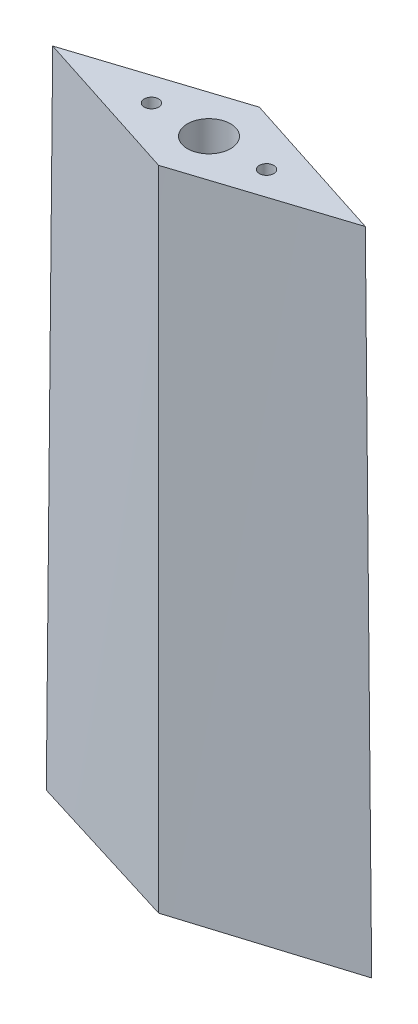
SolidWorks part; units mm, degrees
ref_plane "Front Plane" through (0, 0, 0) normal (0, 0, 1) x (1, 0, 0)
ref_plane "Top Plane" through (0, 0, 0) normal (0, 1, 0) x (1, 0, 0)
ref_plane "Right Plane" through (0, 0, 0) normal (1, 0, 0) x (0, 0, -1)
sketch "Sketch1" plane through (0, 0, 0) normal (0, 0, 1) x (1, 0, 0)
  line L0 (142.4212, 465.168) -> (219.716, 465.168)
  line L1 (219.716, 465.168) -> (213.5025, 1096.9676)
  line L2 (213.5025, 1096.9676) -> (181.0686, 1174.3372)
  line L3 (181.0686, 1174.3372) -> (148.6348, 1096.9676)
  line L4 (148.6348, 1096.9676) -> (142.4212, 465.168)
  point P2 (181.0686, 465.168)
extrude "Boss-Extrude1" add sketch "Sketch1" along normal blind 11.1125 and the other way blind 11.1125
sketch "Sketch2" plane through (0, 465.168, 0) normal (0, -1, 0) x (1, 0, 0)
  line L0 (142.4212, 0) -> (181.0686, 11.1125)
  line L1 (142.4212, -11.1125) -> (142.4212, 11.1125) construction
  line L2 (142.4212, 11.1125) -> (219.716, 11.1125) construction
  line L3 (181.0686, 11.1125) -> (219.716, 0)
  line L4 (219.716, -11.1125) -> (219.716, 11.1125) construction
  line L8 (142.4212, 0) -> (137.8486, 0)
  line L9 (137.8486, 0) -> (137.8486, 15.2584)
  line L10 (137.8486, 15.2584) -> (222.7051, 15.2584)
  line L11 (222.7051, 15.2584) -> (222.7051, 0)
  line L12 (222.7051, 0) -> (219.716, 0)
ref_plane "Plane1" through (0, 1096.9676, 0) normal (0, 1, 0) x (1, 0, 0)
sketch "Sketch3" plane through (0, 1096.9676, 0) normal (0, 1, 0) x (1, 0, 0)
  line L1 (148.6348, 11.1125) -> (148.6348, -11.1125) construction
  line L3 (213.5025, 11.1125) -> (213.5025, -11.1125) construction
  line L4 (213.5025, 0) -> (181.0686, -11.1125)
  line L5 (181.0686, -11.1125) -> (148.6348, 0)
  line L6 (148.6348, 0) -> (137.8486, 0)
  line L7 (137.8486, 0) -> (137.8486, -15.2584)
  line L8 (137.8486, -15.2584) -> (222.7051, -15.2584)
  line L9 (222.7051, -15.2584) -> (222.7051, 0)
  line L10 (222.7051, 0) -> (213.5025, 0)
loft "Cut-Loft1" cut profiles "Sketch2", "Sketch3"
mirror "Mirror1" about plane through (0, 0, 0) normal (0, 0, 1) of "Cut-Loft1"
ref_plane "Plane2" through (-32.1031, 13.4578, 93.6987) normal (-0.3212, 0.1346, 0.9374) x (0.947, 0.0457, 0.3179)
sketch "Sketch5" plane through (-32.1031, 13.4578, 93.6987) normal (-0.3212, 0.1346, 0.9374) x (0.947, 0.0457, 0.3179)
  line L1 (164.4105, 1280.8293) -> (274.288, 1280.8293)
  line L2 (164.4105, 1280.8293) -> (164.4105, 997.7782)
  line L3 (164.4105, 997.7782) -> (274.288, 997.7782)
  line L4 (274.288, 1280.8293) -> (274.288, 997.7782)
extrude "Cut-Extrude2" cut sketch "Sketch5" along normal through all
ref_plane "Plane3" through (69.4583, 29.1174, 202.7265) normal (0.3212, 0.1346, 0.9374) x (0.947, -0.0457, -0.3179)
sketch "Sketch6" plane through (69.4583, 29.1174, 202.7265) normal (0.3212, 0.1346, 0.9374) x (0.947, -0.0457, -0.3179)
  line L1 (57.1921, 1173.3831) -> (206.3136, 1173.3831)
  line L2 (57.1921, 1173.3831) -> (57.1921, 1064.4614)
  line L3 (57.1921, 1064.4614) -> (206.3136, 1064.4614)
  line L4 (206.3136, 1173.3831) -> (206.3136, 1064.4614)
extrude "Cut-Extrude3" cut sketch "Sketch6" along normal through all
mirror "Mirror2" about plane through (0, 0, 0) normal (0, 0, 1) of "Cut-Extrude2", "Cut-Extrude3"
sketch "Sketch7" plane through (0, 465.168, 0) normal (0, -1, 0) x (1, 0, 0)
  circle A0 centre (181.0686, 0) radius 4.7625
  dimension "D1" = 9.525
extrude "Cut-Extrude4" cut sketch "Sketch7" against normal blind 635
sketch "Sketch8" plane through (0, 0, 0) normal (0, 0, 1) x (1, 0, 0)
  line L0 (105.7103, 602.8372) -> (255.485, 602.8372)
  line L1 (105.7103, 1207.5881) -> (255.485, 1207.5881)
  line L2 (105.7103, 1207.5881) -> (105.7103, 454.0044)
  line L3 (105.7103, 454.0044) -> (255.485, 454.0044)
  line L4 (255.485, 1207.5881) -> (255.485, 454.0044)
  line L5 (255.485, 745.7122) -> (105.7103, 745.7122)
  line L6 (105.7103, 888.5872) -> (255.485, 888.5872)
  line L7 (255.485, 1031.4622) -> (105.7103, 1031.4622)
  dimension "D1" = 142.875
  dimension "D2" = 142.875
  dimension "D3" = 142.875
  dimension "D4" = 142.875
extrude "Cut-Extrude8" cut sketch "Sketch8" against normal through all and the other way through all contours L4 L0 L2 L3 | L4 L7 L2 L6 | L7 L4 L1 L2 | L4 L5 L2 L0
sketch "Sketch13" plane through (0, 745.7122, 0) normal (0, -1, 0) x (1, 0, 0)
  circle A0 centre (168.3686, 0) radius 1.5875
  circle A1 centre (193.7686, 0) radius 1.5875
  circle A2 centre (181.0686, 0) radius 4.7625 construction
  dimension "D1" = 3.175
  dimension "D2" = 12.7
  dimension "D3" = 12.7
extrude "Cut-Extrude11" cut sketch "Sketch13" against normal blind 12.7
sketch "Sketch14" plane through (0, 888.5872, 0) normal (0, 1, 0) x (1, 0, 0)
  circle A0 centre (168.3686, 0) radius 1.5875
  circle A1 centre (193.7686, 0) radius 1.5875
  circle A2 centre (181.0686, 0) radius 4.7625 construction
  dimension "D1" = 3.175
  dimension "D3" = 12.7
  dimension "D2" = 12.7
extrude "Cut-Extrude12" cut sketch "Sketch14" against normal blind 12.7
